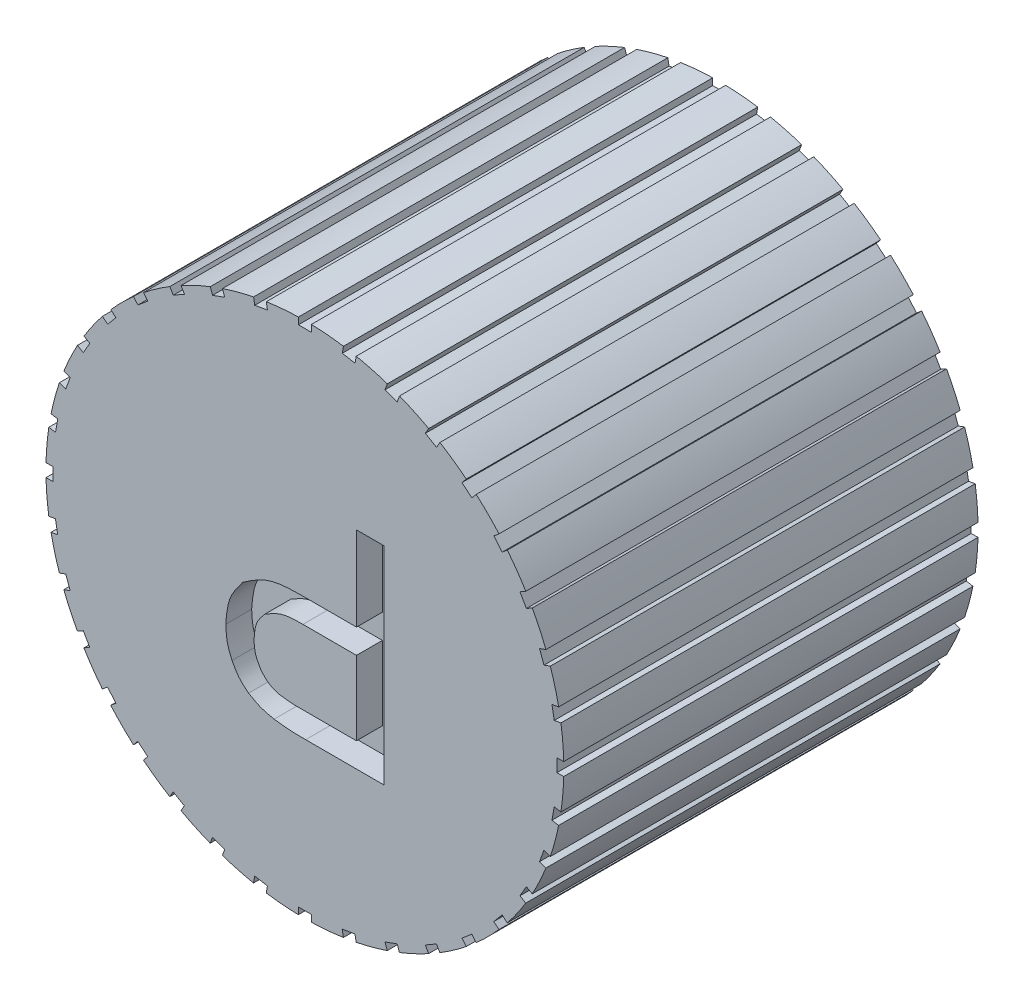
SolidWorks part; units mm, degrees
ref_plane "Front Plane" through (0, 0, 0) normal (0, 0, 1) x (1, 0, 0)
ref_plane "Top Plane" through (0, 0, 0) normal (0, 1, 0) x (1, 0, 0)
ref_plane "Right Plane" through (0, 0, 0) normal (1, 0, 0) x (0, 0, -1)
sketch "Sketch1" plane through (0, 0, 0) normal (0, 1, 0) x (1, 0, 0)
  line L0 (10, 0) -> (0, 0)
  line L1 (0, 0) -> (0, -16)
  line L2 (0, -16) -> (10, -16)
  line L3 (10, -16) -> (10, 0)
  line L4 (0, 0) -> (0, -16) construction
revolve "Revolve1" add sketch "Sketch1" angle 360 about L4
sketch "Sketch2" plane through (0, 0, 0) normal (0, 0, -1) x (-1, 0, 0)
  line L0 (3.183, 9.4799) -> (3.0936, 9.2344)
  line L1 (3.0936, 9.2344) -> (3.5632, 9.0635)
  line L2 (3.5632, 9.0635) -> (3.6526, 9.3091)
  arc A0 (3.6526, 9.3091) -> (3.183, 9.4799) centre (0, 0) ccw
extrude "Cut-Extrude1" cut sketch "Sketch2" against normal blind 16
sketch "Sketch3" plane through (0, 0, 0) normal (0, 0, -1) x (-1, 0, 0)
  line L0 (4.7808, 8.7832) -> (4.6502, 8.5569)
  line L1 (4.6502, 8.5569) -> (5.0829, 8.307)
  line L2 (5.0829, 8.307) -> (5.2136, 8.5334)
  arc A0 (5.2136, 8.5334) -> (4.7808, 8.7832) centre (0, 0) ccw
extrude "Cut-Extrude2" cut sketch "Sketch3" against normal blind 16
sketch "Sketch4" plane through (0, 0, 0) normal (0, 0, -1) x (-1, 0, 0)
  line L0 (6.2334, 7.8195) -> (6.0654, 7.6194)
  line L1 (6.0654, 7.6194) -> (6.4482, 7.2982)
  line L2 (6.4482, 7.2982) -> (6.6162, 7.4984)
  arc A0 (6.6162, 7.4984) -> (6.2334, 7.8195) centre (0, 0) ccw
extrude "Cut-Extrude3" cut sketch "Sketch4" against normal blind 16
sketch "Sketch5" plane through (0, 0, 0) normal (0, 0, -1) x (-1, 0, 0)
  line L0 (7.4965, 6.6183) -> (7.2963, 6.4504)
  line L1 (7.2963, 6.4504) -> (7.6176, 6.0676)
  line L2 (7.6176, 6.0676) -> (7.8178, 6.2356)
  arc A0 (7.8178, 6.2356) -> (7.4965, 6.6183) centre (0, 0) ccw
extrude "Cut-Extrude4" cut sketch "Sketch5" against normal blind 16
sketch "Sketch6" plane through (0, 0, 0) normal (0, 0, -1) x (-1, 0, 0)
  line L0 (8.5319, 5.216) -> (8.3056, 5.0854)
  line L1 (8.3056, 5.0854) -> (8.5554, 4.6526)
  line L2 (8.5554, 4.6526) -> (8.7818, 4.7833)
  arc A0 (8.7818, 4.7833) -> (8.5319, 5.216) centre (0, 0) ccw
extrude "Cut-Extrude5" cut sketch "Sketch6" against normal blind 16
sketch "Sketch7" plane through (0, 0, 0) normal (0, 0, -1) x (-1, 0, 0)
  line L0 (9.308, 3.6552) -> (9.0625, 3.5659)
  line L1 (9.0625, 3.5659) -> (9.2334, 3.0963)
  line L2 (9.2334, 3.0963) -> (9.479, 3.1857)
  arc A0 (9.479, 3.1857) -> (9.308, 3.6552) centre (0, 0) ccw
extrude "Cut-Extrude6" cut sketch "Sketch7" against normal blind 16
sketch "Sketch8" plane through (0, 0, 0) normal (0, 0, -1) x (-1, 0, 0)
  line L0 (9.8013, 1.9834) -> (9.544, 1.938)
  line L1 (9.544, 1.938) -> (9.6308, 1.4459)
  line L2 (9.6308, 1.4459) -> (9.8882, 1.4913)
  arc A0 (9.8882, 1.4913) -> (9.8013, 1.9834) centre (0, 0) ccw
extrude "Cut-Extrude7" cut sketch "Sketch8" against normal blind 16
sketch "Sketch9" plane through (0, 0, 0) normal (0, 0, -1) x (-1, 0, 0)
  line L0 (9.9968, 0.2513) -> (9.7356, 0.2513)
  line L1 (9.7356, 0.2513) -> (9.7356, -0.2484)
  line L2 (9.7356, -0.2484) -> (9.9969, -0.2484)
  arc A0 (9.9969, -0.2484) -> (9.9968, 0.2513) centre (0, 0) ccw
extrude "Cut-Extrude8" cut sketch "Sketch9" against normal blind 16
sketch "Sketch10" plane through (0, 0, 0) normal (0, 0, -1) x (-1, 0, 0)
  line L0 (9.8886, -1.4885) -> (9.6313, -1.4431)
  line L1 (9.6313, -1.4431) -> (9.5445, -1.9352)
  line L2 (9.5445, -1.9352) -> (9.8019, -1.9806)
  arc A0 (9.8019, -1.9806) -> (9.8886, -1.4885) centre (0, 0) ccw
extrude "Cut-Extrude9" cut sketch "Sketch10" against normal blind 16
sketch "Sketch11" plane through (0, 0, 0) normal (0, 0, -1) x (-1, 0, 0)
  line L0 (9.4799, -3.183) -> (9.2344, -3.0936)
  line L1 (9.2344, -3.0936) -> (9.0635, -3.5632)
  line L2 (9.0635, -3.5632) -> (9.3091, -3.6526)
  arc A0 (9.3091, -3.6526) -> (9.4799, -3.183) centre (0, 0) ccw
extrude "Cut-Extrude10" cut sketch "Sketch11" against normal blind 16
sketch "Sketch12" plane through (0, 0, 0) normal (0, 0, -1) x (-1, 0, 0)
  line L0 (8.7832, -4.7808) -> (8.5569, -4.6502)
  line L1 (8.5569, -4.6502) -> (8.307, -5.0829)
  line L2 (8.307, -5.0829) -> (8.5334, -5.2136)
  arc A0 (8.5334, -5.2136) -> (8.7832, -4.7808) centre (0, 0) ccw
extrude "Cut-Extrude11" cut sketch "Sketch12" against normal blind 16
sketch "Sketch13" plane through (0, 0, 0) normal (0, 0, -1) x (-1, 0, 0)
  line L0 (7.8195, -6.2334) -> (7.6194, -6.0654)
  line L1 (7.6194, -6.0654) -> (7.2982, -6.4482)
  line L2 (7.2982, -6.4482) -> (7.4984, -6.6162)
  arc A0 (7.4984, -6.6162) -> (7.8195, -6.2334) centre (0, 0) ccw
extrude "Cut-Extrude12" cut sketch "Sketch13" against normal blind 16
sketch "Sketch14" plane through (0, 0, 0) normal (0, 0, -1) x (-1, 0, 0)
  line L0 (6.6183, -7.4965) -> (6.4504, -7.2963)
  line L1 (6.4504, -7.2963) -> (6.0676, -7.6176)
  line L2 (6.0676, -7.6176) -> (6.2356, -7.8178)
  arc A0 (6.2356, -7.8178) -> (6.6183, -7.4965) centre (0, 0) ccw
extrude "Cut-Extrude13" cut sketch "Sketch14" against normal blind 16
sketch "Sketch15" plane through (0, 0, 0) normal (0, 0, -1) x (-1, 0, 0)
  line L0 (5.216, -8.5319) -> (5.0854, -8.3056)
  line L1 (5.0854, -8.3056) -> (4.6526, -8.5554)
  line L2 (4.6526, -8.5554) -> (4.7833, -8.7818)
  arc A0 (4.7833, -8.7818) -> (5.216, -8.5319) centre (0, 0) ccw
extrude "Cut-Extrude14" cut sketch "Sketch15" against normal blind 16
sketch "Sketch16" plane through (0, 0, 0) normal (0, 0, -1) x (-1, 0, 0)
  line L0 (3.6552, -9.308) -> (3.5659, -9.0625)
  line L1 (3.5659, -9.0625) -> (3.0963, -9.2334)
  line L2 (3.0963, -9.2334) -> (3.1857, -9.479)
  arc A0 (3.1857, -9.479) -> (3.6552, -9.308) centre (0, 0) ccw
extrude "Cut-Extrude15" cut sketch "Sketch16" against normal blind 16
sketch "Sketch17" plane through (0, 0, 0) normal (0, 0, -1) x (-1, 0, 0)
  line L0 (1.9834, -9.8013) -> (1.938, -9.544)
  line L1 (1.938, -9.544) -> (1.4459, -9.6308)
  line L2 (1.4459, -9.6308) -> (1.4913, -9.8882)
  arc A0 (1.4913, -9.8882) -> (1.9834, -9.8013) centre (0, 0) ccw
extrude "Cut-Extrude16" cut sketch "Sketch17" against normal blind 16
sketch "Sketch18" plane through (0, 0, 0) normal (0, 0, -1) x (-1, 0, 0)
  line L0 (0.2513, -9.9968) -> (0.2513, -9.7356)
  line L1 (0.2513, -9.7356) -> (-0.2484, -9.7356)
  line L2 (-0.2484, -9.7356) -> (-0.2484, -9.9969)
  arc A0 (-0.2484, -9.9969) -> (0.2513, -9.9968) centre (0, 0) ccw
extrude "Cut-Extrude17" cut sketch "Sketch18" against normal blind 16
sketch "Sketch19" plane through (0, 0, 0) normal (0, 0, -1) x (-1, 0, 0)
  line L0 (-1.4885, -9.8886) -> (-1.4431, -9.6313)
  line L1 (-1.4431, -9.6313) -> (-1.9352, -9.5445)
  line L2 (-1.9352, -9.5445) -> (-1.9806, -9.8019)
  arc A0 (-1.9806, -9.8019) -> (-1.4885, -9.8886) centre (0, 0) ccw
extrude "Cut-Extrude18" cut sketch "Sketch19" against normal blind 16
sketch "Sketch20" plane through (0, 0, 0) normal (0, 0, -1) x (-1, 0, 0)
  line L0 (-3.183, -9.4799) -> (-3.0936, -9.2344)
  line L1 (-3.0936, -9.2344) -> (-3.5632, -9.0635)
  line L2 (-3.5632, -9.0635) -> (-3.6526, -9.3091)
  arc A0 (-3.6526, -9.3091) -> (-3.183, -9.4799) centre (0, 0) ccw
extrude "Cut-Extrude19" cut sketch "Sketch20" against normal blind 16
sketch "Sketch21" plane through (0, 0, 0) normal (0, 0, -1) x (-1, 0, 0)
  line L0 (-4.7808, -8.7832) -> (-4.6502, -8.5569)
  line L1 (-4.6502, -8.5569) -> (-5.0829, -8.307)
  line L2 (-5.0829, -8.307) -> (-5.2136, -8.5334)
  arc A0 (-5.2136, -8.5334) -> (-4.7808, -8.7832) centre (0, 0) ccw
extrude "Cut-Extrude20" cut sketch "Sketch21" against normal blind 16
sketch "Sketch22" plane through (0, 0, 0) normal (0, 0, -1) x (-1, 0, 0)
  line L0 (-6.2334, -7.8195) -> (-6.0654, -7.6194)
  line L1 (-6.0654, -7.6194) -> (-6.4482, -7.2982)
  line L2 (-6.4482, -7.2982) -> (-6.6162, -7.4984)
  arc A0 (-6.6162, -7.4984) -> (-6.2334, -7.8195) centre (0, 0) ccw
extrude "Cut-Extrude21" cut sketch "Sketch22" against normal blind 16
sketch "Sketch23" plane through (0, 0, 0) normal (0, 0, -1) x (-1, 0, 0)
  line L0 (-7.4965, -6.6183) -> (-7.2963, -6.4504)
  line L1 (-7.2963, -6.4504) -> (-7.6176, -6.0676)
  line L2 (-7.6176, -6.0676) -> (-7.8178, -6.2356)
  arc A0 (-7.8178, -6.2356) -> (-7.4965, -6.6183) centre (0, 0) ccw
extrude "Cut-Extrude22" cut sketch "Sketch23" against normal blind 16
sketch "Sketch24" plane through (0, 0, 0) normal (0, 0, -1) x (-1, 0, 0)
  line L0 (-8.5319, -5.216) -> (-8.3056, -5.0854)
  line L1 (-8.3056, -5.0854) -> (-8.5554, -4.6526)
  line L2 (-8.5554, -4.6526) -> (-8.7818, -4.7833)
  arc A0 (-8.7818, -4.7833) -> (-8.5319, -5.216) centre (0, 0) ccw
extrude "Cut-Extrude23" cut sketch "Sketch24" against normal blind 16
sketch "Sketch25" plane through (0, 0, 0) normal (0, 0, -1) x (-1, 0, 0)
  line L0 (-9.308, -3.6552) -> (-9.0625, -3.5659)
  line L1 (-9.0625, -3.5659) -> (-9.2334, -3.0963)
  line L2 (-9.2334, -3.0963) -> (-9.479, -3.1857)
  arc A0 (-9.479, -3.1857) -> (-9.308, -3.6552) centre (0, 0) ccw
extrude "Cut-Extrude24" cut sketch "Sketch25" against normal blind 16
sketch "Sketch26" plane through (0, 0, 0) normal (0, 0, -1) x (-1, 0, 0)
  line L0 (-9.8013, -1.9834) -> (-9.544, -1.938)
  line L1 (-9.544, -1.938) -> (-9.6308, -1.4459)
  line L2 (-9.6308, -1.4459) -> (-9.8882, -1.4913)
  arc A0 (-9.8882, -1.4913) -> (-9.8013, -1.9834) centre (0, 0) ccw
extrude "Cut-Extrude25" cut sketch "Sketch26" against normal blind 16
sketch "Sketch27" plane through (0, 0, 0) normal (0, 0, -1) x (-1, 0, 0)
  line L0 (-9.9968, -0.2513) -> (-9.7356, -0.2513)
  line L1 (-9.7356, -0.2513) -> (-9.7356, 0.2484)
  line L2 (-9.7356, 0.2484) -> (-9.9969, 0.2484)
  arc A0 (-9.9969, 0.2484) -> (-9.9968, -0.2513) centre (0, 0) ccw
extrude "Cut-Extrude26" cut sketch "Sketch27" against normal blind 16
sketch "Sketch28" plane through (0, 0, 0) normal (0, 0, -1) x (-1, 0, 0)
  line L0 (-9.8886, 1.4885) -> (-9.6313, 1.4431)
  line L1 (-9.6313, 1.4431) -> (-9.5445, 1.9352)
  line L2 (-9.5445, 1.9352) -> (-9.8019, 1.9806)
  arc A0 (-9.8019, 1.9806) -> (-9.8886, 1.4885) centre (0, 0) ccw
extrude "Cut-Extrude27" cut sketch "Sketch28" against normal blind 16
sketch "Sketch29" plane through (0, 0, 0) normal (0, 0, -1) x (-1, 0, 0)
  line L0 (-9.4799, 3.183) -> (-9.2344, 3.0936)
  line L1 (-9.2344, 3.0936) -> (-9.0635, 3.5632)
  line L2 (-9.0635, 3.5632) -> (-9.3091, 3.6526)
  arc A0 (-9.3091, 3.6526) -> (-9.4799, 3.183) centre (0, 0) ccw
extrude "Cut-Extrude28" cut sketch "Sketch29" against normal blind 16
sketch "Sketch30" plane through (0, 0, 0) normal (0, 0, -1) x (-1, 0, 0)
  line L0 (-8.7832, 4.7808) -> (-8.5569, 4.6502)
  line L1 (-8.5569, 4.6502) -> (-8.307, 5.0829)
  line L2 (-8.307, 5.0829) -> (-8.5334, 5.2136)
  arc A0 (-8.5334, 5.2136) -> (-8.7832, 4.7808) centre (0, 0) ccw
extrude "Cut-Extrude29" cut sketch "Sketch30" against normal blind 16
sketch "Sketch31" plane through (0, 0, 0) normal (0, 0, -1) x (-1, 0, 0)
  line L0 (-7.8195, 6.2334) -> (-7.6194, 6.0654)
  line L1 (-7.6194, 6.0654) -> (-7.2982, 6.4482)
  line L2 (-7.2982, 6.4482) -> (-7.4984, 6.6162)
  arc A0 (-7.4984, 6.6162) -> (-7.8195, 6.2334) centre (0, 0) ccw
extrude "Cut-Extrude30" cut sketch "Sketch31" against normal blind 16
sketch "Sketch32" plane through (0, 0, 0) normal (0, 0, -1) x (-1, 0, 0)
  line L0 (-6.6183, 7.4965) -> (-6.4504, 7.2963)
  line L1 (-6.4504, 7.2963) -> (-6.0676, 7.6176)
  line L2 (-6.0676, 7.6176) -> (-6.2356, 7.8178)
  arc A0 (-6.2356, 7.8178) -> (-6.6183, 7.4965) centre (0, 0) ccw
extrude "Cut-Extrude31" cut sketch "Sketch32" against normal blind 16
sketch "Sketch33" plane through (0, 0, 0) normal (0, 0, -1) x (-1, 0, 0)
  line L0 (-5.216, 8.5319) -> (-5.0854, 8.3056)
  line L1 (-5.0854, 8.3056) -> (-4.6526, 8.5554)
  line L2 (-4.6526, 8.5554) -> (-4.7833, 8.7818)
  arc A0 (-4.7833, 8.7818) -> (-5.216, 8.5319) centre (0, 0) ccw
extrude "Cut-Extrude32" cut sketch "Sketch33" against normal blind 16
sketch "Sketch34" plane through (0, 0, 0) normal (0, 0, -1) x (-1, 0, 0)
  line L0 (-3.6552, 9.308) -> (-3.5659, 9.0625)
  line L1 (-3.5659, 9.0625) -> (-3.0963, 9.2334)
  line L2 (-3.0963, 9.2334) -> (-3.1857, 9.479)
  arc A0 (-3.1857, 9.479) -> (-3.6552, 9.308) centre (0, 0) ccw
extrude "Cut-Extrude33" cut sketch "Sketch34" against normal blind 16
sketch "Sketch35" plane through (0, 0, 0) normal (0, 0, -1) x (-1, 0, 0)
  line L0 (-1.9834, 9.8013) -> (-1.938, 9.544)
  line L1 (-1.938, 9.544) -> (-1.4459, 9.6308)
  line L2 (-1.4459, 9.6308) -> (-1.4913, 9.8882)
  arc A0 (-1.4913, 9.8882) -> (-1.9834, 9.8013) centre (0, 0) ccw
extrude "Cut-Extrude34" cut sketch "Sketch35" against normal blind 16
sketch "Sketch36" plane through (0, 0, 0) normal (0, 0, -1) x (-1, 0, 0)
  line L0 (-0.2513, 9.9968) -> (-0.2513, 9.7356)
  line L1 (-0.2513, 9.7356) -> (0.2484, 9.7356)
  line L2 (0.2484, 9.7356) -> (0.2484, 9.9969)
  arc A0 (0.2484, 9.9969) -> (-0.2513, 9.9968) centre (0, 0) ccw
extrude "Cut-Extrude35" cut sketch "Sketch36" against normal blind 16
sketch "Sketch37" plane through (0, 0, 0) normal (0, 0, -1) x (-1, 0, 0)
  line L0 (1.4885, 9.8886) -> (1.4431, 9.6313)
  line L1 (1.4431, 9.6313) -> (1.9352, 9.5445)
  line L2 (1.9352, 9.5445) -> (1.9806, 9.8019)
  arc A0 (1.9806, 9.8019) -> (1.4885, 9.8886) centre (0, 0) ccw
extrude "Cut-Extrude36" cut sketch "Sketch37" against normal blind 16
ref_plane "Plane1" through (0, 0, 13) normal (0, 0, 1) x (1, 0, 0)
sketch "Sketch38" plane through (0, 0, 13) normal (0, 0, 1) x (1, 0, 0)
  line L0 (3.0496, -4.0027) -> (0.0319, -4)
  line L1 (-0.0566, 0.7477) -> (1.9952, 0.7458)
  line L2 (1.9952, 0.7458) -> (1.9981, 3.9982)
  line L3 (1.9981, 3.9982) -> (3.0568, 3.9973)
  line L4 (3.0568, 3.9973) -> (3.0496, -4.0027)
  arc A0 (0.0319, -4) -> (-1.185, -3.9225) centre (-0.1126, 3.3237) cw
  spline S0 degree 3 poles (-1.185, -3.9225) (-1.2235, -3.9147) (-1.3006, -3.899) (-1.4159, -3.8738) (-1.5304, -3.845) (-1.6435, -3.811) (-1.7544, -3.7697) (-1.8621, -3.7205) (-1.9671, -3.6659) (-2.0702, -3.6078) (-2.1383, -3.5678) (-2.1724, -3.5478) knots 0 0 0 0 0.110986 0.221903 0.332758 0.443719 0.554995 0.666142 0.777406 0.8887 1 1 1 1
  spline S1 degree 3 poles (-2.1724, -3.5478) (-2.2014, -3.5242) (-2.2595, -3.4769) (-2.3452, -3.4044) (-2.428, -3.3285) (-2.5065, -3.2478) (-2.5782, -3.1607) (-2.6429, -3.0682) (-2.7025, -2.9722) (-2.7586, -2.8742) (-2.7948, -2.8081) (-2.8129, -2.7751) knots 0 0 0 0 0.110867 0.221625 0.332283 0.443112 0.554485 0.665741 0.777135 0.888564 1 1 1 1
  spline S2 degree 3 poles (-2.8129, -2.7751) (-2.8414, -2.7058) (-2.8986, -2.5671) (-2.9733, -2.3545) (-3.0218, -2.1339) (-3.044, -1.909) (-3.0511, -1.7587) (-3.0547, -1.6835) knots 0 0 0 0 0.199722 0.399196 0.599258 0.799452 1 1 1 1
  spline S3 degree 3 poles (-3.0547, -1.6835) (-3.0477, -1.5935) (-3.0338, -1.4139) (-3.0015, -1.1464) (-2.9458, -0.8834) (-2.8519, -0.6309) (-2.7198, -0.3955) (-2.5667, -0.1727) (-2.4581, -0.0288) (-2.4038, 0.0431) knots 0 0 0 0 0.143507 0.2866 0.428442 0.570098 0.713348 0.856629 1 1 1 1
  spline S4 degree 3 poles (-2.4038, 0.0431) (-2.3269, 0.0965) (-2.1732, 0.2034) (-1.9374, 0.3561) (-1.6918, 0.4913) (-1.4343, 0.5989) (-1.1662, 0.6701) (-0.8924, 0.7127) (-0.615, 0.7352) (-0.3359, 0.7447) (-0.1497, 0.7467) (-0.0566, 0.7477) knots 0 0 0 0 0.111905 0.223719 0.335717 0.446572 0.556279 0.666369 0.777426 0.888707 1 1 1 1
extrude "Cut-Extrude37" cut sketch "Sketch38" against normal blind 1 from surface at 3 starting at face at (0, 0, 16)
ref_plane "Plane2" through (0, 0, 18) normal (0, 0, -1) x (0, 1, 0)
sketch "Sketch39" plane through (0, 0, 18) normal (0, 0, -1) x (0, 1, 0)
  line L0 (-3.0559, -0.0546) -> (-3.0577, 1.9918)
  line L1 (-3.0577, 1.9918) -> (-0.1982, 1.9944)
  line L2 (-0.1982, 1.9944) -> (-0.1964, -0.0738)
  arc A0 (-2.9841, -1.0422) -> (-3.0559, -0.0546) centre (1.5283, -0.2176) cw
  spline S0 degree 3 poles (-2.5114, -1.7103) (-2.5352, -1.6905) (-2.5828, -1.6509) (-2.6526, -1.5898) (-2.7192, -1.5255) (-2.7805, -1.4566) (-2.8339, -1.3813) (-2.8788, -1.3004) (-2.9175, -1.2159) (-2.9518, -1.1295) (-2.9733, -1.0713) (-2.9841, -1.0422) knots 0 0 0 0 0.111394 0.222774 0.333964 0.444245 0.554264 0.665235 0.776872 0.888409 1 1 1 1
  spline S1 degree 3 poles (-0.1964, -0.0738) (-0.197, -0.1308) (-0.1981, -0.2447) (-0.2033, -0.4155) (-0.2158, -0.5853) (-0.2392, -0.7532) (-0.2777, -0.9179) (-0.3354, -1.0777) (-0.4079, -1.2324) (-0.4903, -1.383) (-0.5481, -1.4818) (-0.5771, -1.5312) knots 0 0 0 0 0.111441 0.222872 0.33409 0.444372 0.554109 0.664377 0.776028 0.888003 1 1 1 1
  spline S2 degree 3 poles (-0.5771, -1.5312) (-0.6106, -1.5601) (-0.6775, -1.618) (-0.7807, -1.7016) (-0.8888, -1.7783) (-1.0039, -1.8436) (-1.1274, -1.8915) (-1.2562, -1.9227) (-1.3874, -1.9424) (-1.5194, -1.9546) (-1.6076, -1.9604) (-1.6517, -1.9633) knots 0 0 0 0 0.111394 0.222725 0.334165 0.444661 0.554941 0.66642 0.777581 0.888729 1 1 1 1
  spline S3 degree 3 poles (-1.6517, -1.9633) (-1.6855, -1.9614) (-1.753, -1.9577) (-1.8541, -1.95) (-1.9544, -1.9379) (-2.0533, -1.9193) (-2.1499, -1.8915) (-2.2434, -1.854) (-2.3344, -1.8097) (-2.4235, -1.761) (-2.4821, -1.7272) (-2.5114, -1.7103) knots 0 0 0 0 0.111519 0.223027 0.33434 0.444774 0.554758 0.665246 0.776716 0.88835 1 1 1 1
extrude "Boss-Extrude1" add sketch "Sketch39" against normal blind 1 from surface at 3 starting at face at (-0.0901, -0.7355, 15)
hole_wizard "Ø6.0 (6) Diameter Hole1" positions "Sketch41" profile "Sketch40" hole size "Ø6.0" standard "ANSI Metric"
sketch "Sketch41" plane through (0, 0, 0) normal (0, 0, -1) x (-1, 0, 0)
  point P0 (0, 0)
sketch "Sketch40" plane through (0, 0, 0) normal (1, 0, 0) x (0, 1, 0)
  line L0 (0, 0) -> (0, 14)
  line L1 (0, 14) -> (3, 14)
  line L2 (3, 14) -> (3, 0)
  line L5 (3, 0) -> (0, 0)
  line L10 (0, 14) -> (-3, 14) construction
  line L11 (0, -6.35) -> (0, 107.95) construction
  dimension "Hole Dia." = 6
  dimension "Hole Depth" = 14
  dimension "Drill Angle" = 180
